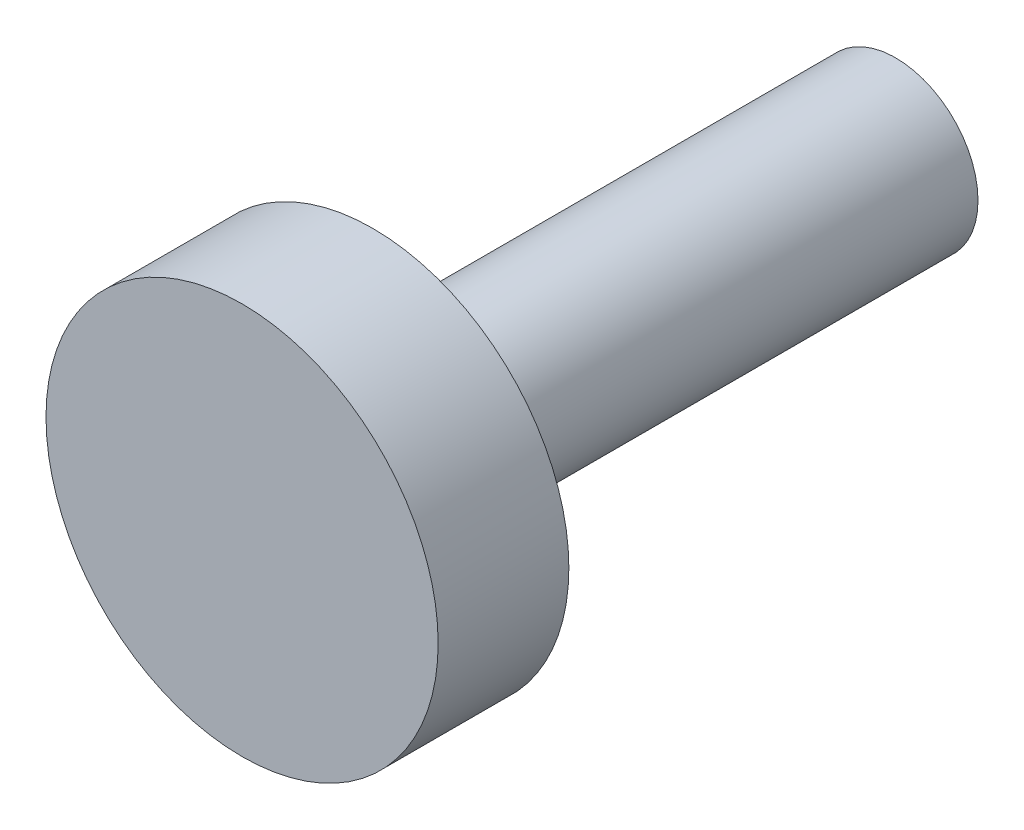
SolidWorks part; units mm, degrees
ref_plane "Front Plane" through (0, 0, 0) normal (0, 0, 1) x (1, 0, 0)
ref_plane "Top Plane" through (0, 0, 0) normal (0, 1, 0) x (1, 0, 0)
ref_plane "Right Plane" through (0, 0, 0) normal (1, 0, 0) x (0, 0, -1)
sketch "Sketch1" plane through (0, 0, 0) normal (0, 0, 1) x (1, 0, 0)
  circle A0 centre (0, 0) radius 9.525
  dimension "D1" = 19.05
extrude "Boss-Extrude1" add sketch "Sketch1" along normal blind 6.35
sketch "Sketch2" plane through (0, 0, 0) normal (0, 0, 1) x (1, 0, 0)
  circle A0 centre (0, 0) radius 4
  dimension "D1" = 8
extrude "Boss-Extrude2" add sketch "Sketch2" against normal blind 25.4
